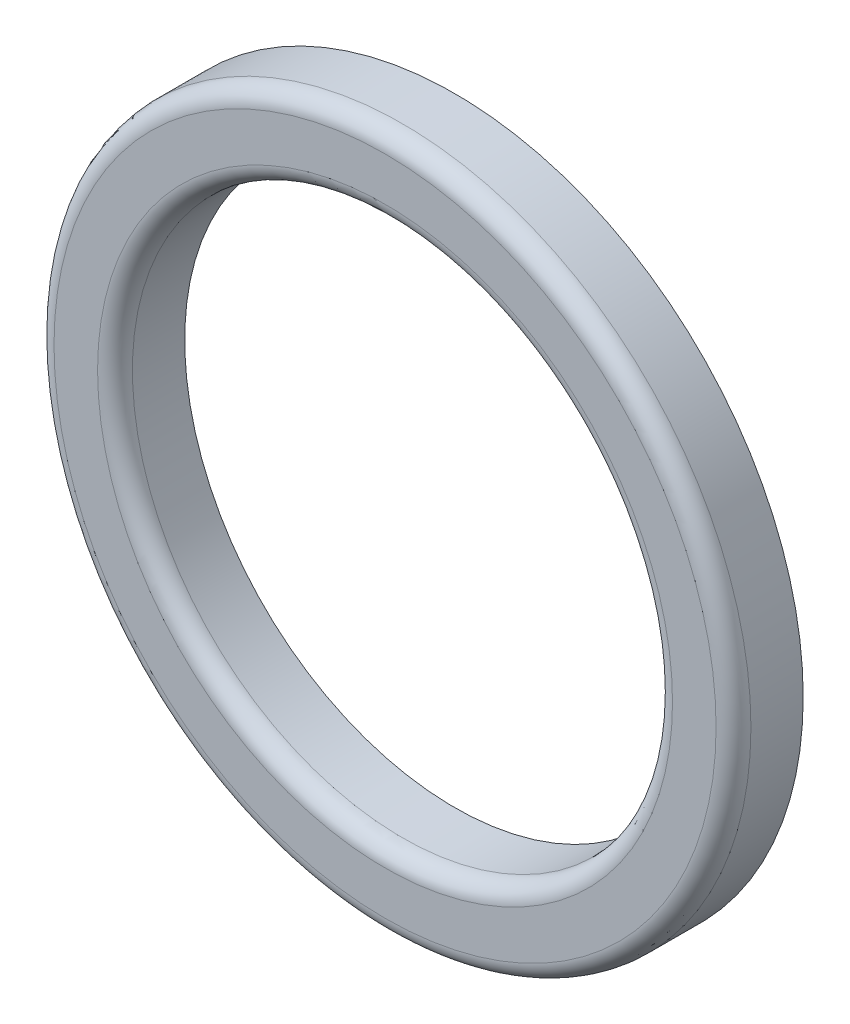
SolidWorks part; units mm, degrees
ref_plane "Přední rovina" through (0, 0, 0) normal (0, 0, 1) x (1, 0, 0)
ref_plane "Horní rovina" through (0, 0, 0) normal (0, 1, 0) x (1, 0, 0)
ref_plane "Pravá rovina" through (0, 0, 0) normal (1, 0, 0) x (0, 0, -1)
sketch "Skica1" plane through (0, 0, 0) normal (0, 0, 1) x (1, 0, 0)
  circle A0 centre (0, 0) radius 7.75
  circle A1 centre (0, 0) radius 10
  dimension "D1" = 20
  dimension "D2" = 15.5
extrude "Přidat vysunutím1" add sketch "Skica1" along normal blind 2
fillet "Zaoblit1" radius 0.5 2 edges at (7.75, 0, 2) (10, 0, 2)
